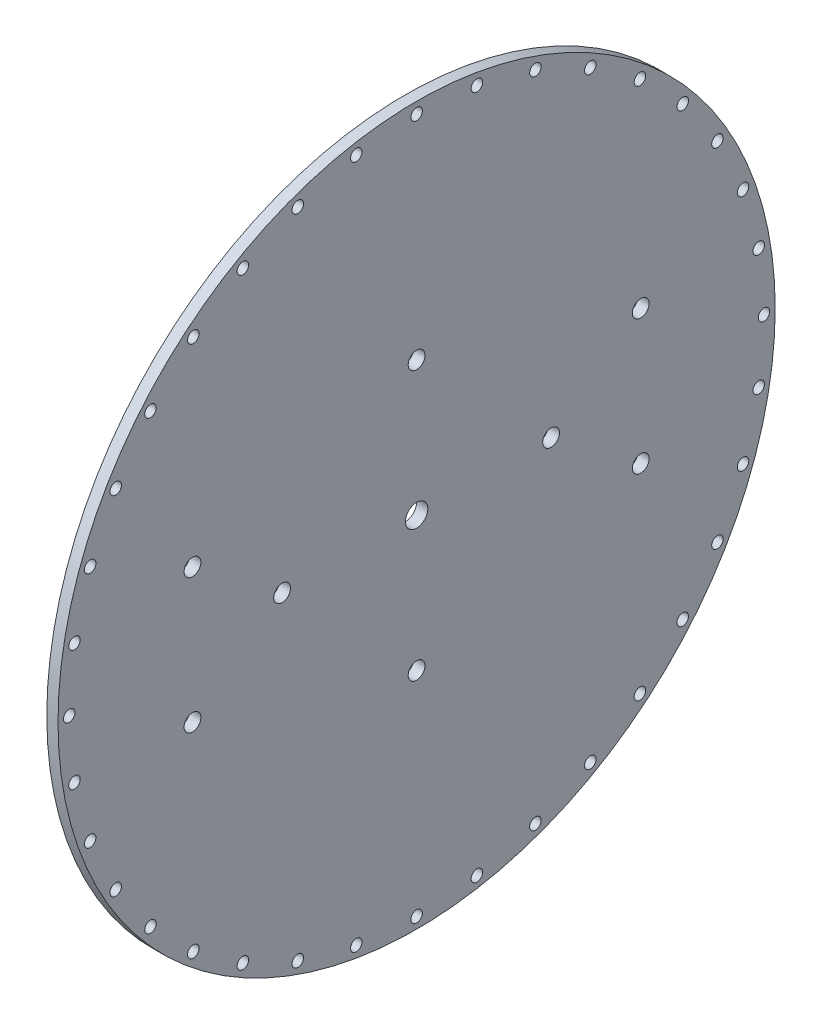
SolidWorks part; units mm, degrees
material "6061-T6 (SS)"
ref_plane "Front" through (0, 0, 0) normal (0, 0, 1) x (1, 0, 0)
ref_plane "Top" through (0, 0, 0) normal (0, 1, 0) x (1, 0, 0)
ref_plane "Right" through (0, 0, 0) normal (1, 0, 0) x (0, 0, -1)
sketch "Sketch1" plane through (0, 0, 0) normal (1, 0, 0) x (0, 0, -1)
  circle A0 centre (0, 0) radius 203.2
  dimension "D1" = 406.4
extrude "Boss-Extrude1" add sketch "Sketch1" along normal blind 6.35
hole_wizard "F (0.257) Diameter Hole1" positions "Sketch2" profile "Sketch3" hole size "F" standard "ANSI Inch"
sketch "Sketch2" plane through (6.35, 0, 0) normal (1, 0, 0) x (0, 0, -1)
  circle A0 centre (0, 0) radius 203.2 construction
  point P0 (-196.85, 0)
  dimension "D1" = 196.85
  dimension "D2" = 0
sketch "Sketch3" plane through (6.35, 0, 196.85) normal (0, 1, 0) x (0, 0, -1)
  line L0 (0, 0) -> (0, 6.35)
  line L1 (0, 6.35) -> (3.2639, 6.35)
  line L2 (3.2639, 6.35) -> (3.2639, 0)
  line L5 (3.2639, 0) -> (0, 0)
  line L11 (0, -6.35) -> (0, 107.95) construction
  dimension "Thru Hole Dia." = 6.5278
  dimension "Thru Hole Depth" = 6.35
pattern_circular "CirPattern1" count 36 over 360 of "F (0.257) Diameter Hole1"
hole_wizard "1/2 (0.5) Diameter Hole1" positions "Sketch4" profile "Sketch5" hole size "1/2" standard "ANSI Inch"
sketch "Sketch4" plane through (6.35, 0, 0) normal (1, 0, 0) x (0, 0, -1)
  point P0 (0, 0)
sketch "Sketch5" plane through (6.35, 0, 0) normal (0, 1, 0) x (0, 0, -1)
  line L0 (0, 0) -> (0, 6.35)
  line L1 (0, 6.35) -> (6.35, 6.35)
  line L2 (6.35, 6.35) -> (6.35, 0)
  line L5 (6.35, 0) -> (0, 0)
  line L11 (0, -6.35) -> (0, 107.95) construction
  dimension "Thru Hole Dia." = 12.7
  dimension "Thru Hole Depth" = 6.35
hole_wizard "3/8 (0.375) Diameter Hole1" positions "Sketch6" profile "Sketch7" hole size "3/8" standard "ANSI Inch"
sketch "Sketch6" plane through (6.35, 0, 0) normal (1, 0, 0) x (0, 0, -1)
  circle A0 centre (0, 0) radius 6.35 construction
  point P2 (0, -76.2)
  dimension "D1" = 0
  dimension "D2" = 76.2
sketch "Sketch7" plane through (6.35, -76.2, 0) normal (0, 1, 0) x (0, 0, -1)
  line L0 (0, 0) -> (0, 6.35)
  line L1 (0, 6.35) -> (4.7625, 6.35)
  line L2 (4.7625, 6.35) -> (4.7625, 0)
  line L5 (4.7625, 0) -> (0, 0)
  line L11 (0, -6.35) -> (0, 107.95) construction
  dimension "Thru Hole Dia." = 9.525
  dimension "Thru Hole Depth" = 6.35
pattern_circular "CirPattern2" count 4 over 360 of "3/8 (0.375) Diameter Hole1"
hole_wizard "3/8 (0.375) Diameter Hole2" positions "Sketch8" profile "Sketch9" hole size "3/8" standard "ANSI Inch"
sketch "Sketch8" plane through (6.35, 0, 0) normal (1, 0, 0) x (0, 0, -1)
  circle A1 centre (0, 0) radius 6.35 construction
  circle A2 centre (0, 0) radius 203.2 construction
  point P0 (-127, -38.1)
  dimension "D1" = 127
  dimension "D2" = 38.1
sketch "Sketch9" plane through (6.35, -38.1, 127) normal (0, 1, 0) x (0, 0, -1)
  line L0 (0, 0) -> (0, 6.35)
  line L1 (0, 6.35) -> (4.7625, 6.35)
  line L2 (4.7625, 6.35) -> (4.7625, 0)
  line L5 (4.7625, 0) -> (0, 0)
  line L11 (0, -6.35) -> (0, 107.95) construction
  dimension "Thru Hole Dia." = 9.525
  dimension "Thru Hole Depth" = 6.35
sketch "Sketch10" plane through (6.35, 0, 0) normal (1, 0, 0) x (0, 0, -1)
  line L0 (-76.2, 0) -> (76.2, 0) construction
  line L1 (0, 76.2) -> (0, -76.2) construction
pattern_linear "LPattern1" count 2 spacing 254 along (0, 0, -1) count 2 spacing 76.2 along (0, 1, 0) of "3/8 (0.375) Diameter Hole2"
